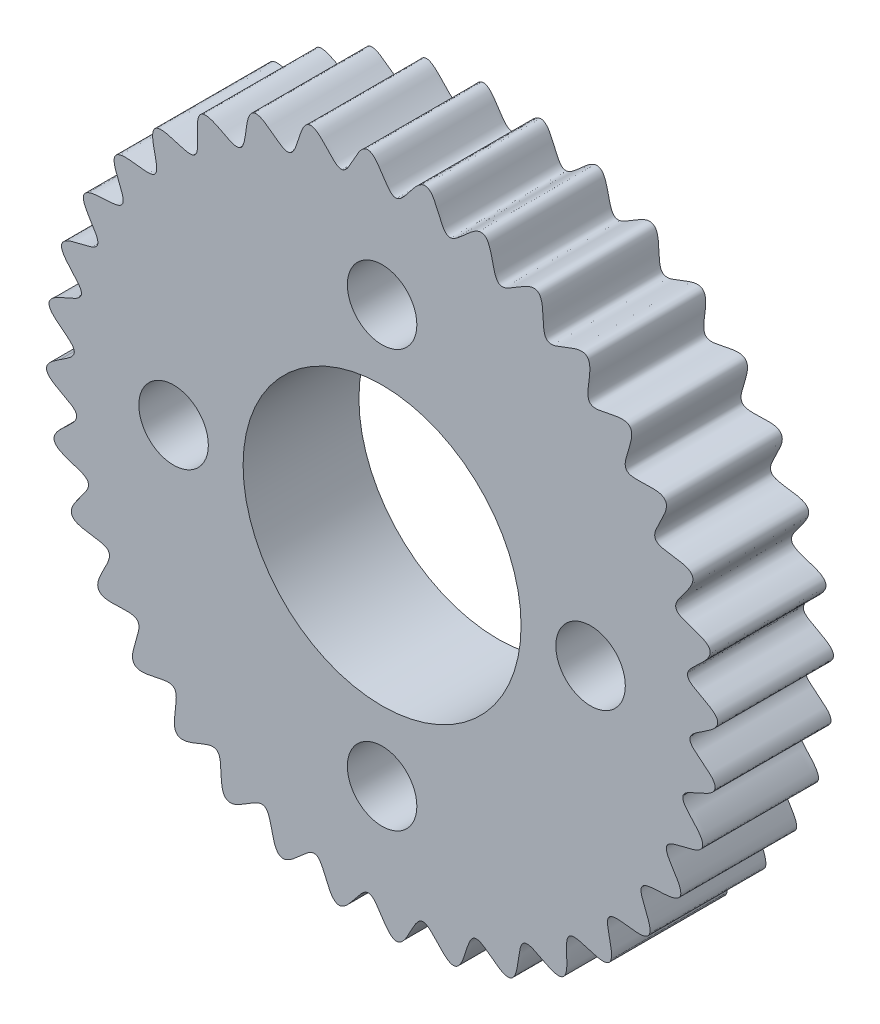
SolidWorks part; units mm, degrees
ref_plane "前视基准面" through (0, 0, 0) normal (0, 0, 1) x (1, 0, 0)
ref_plane "上视基准面" through (0, 0, 0) normal (0, 1, 0) x (1, 0, 0)
ref_plane "右视基准面" through (0, 0, 0) normal (1, 0, 0) x (0, 0, -1)
sketch "草图1" plane through (0, 0, 0) normal (0, 0, 1) x (1, 0, 0)
  circle A0 centre (0, 0) radius 12
  spline S0 degree 4 number of poles 648 (27.5248, -8.9434) -> (-25.354, -8.238) construction
  spline S1 degree 4 number of poles 542 (27.8, 0) -> (-27.8, 0)
  spline S2 degree 4 number of poles 650 (-27.5248, 8.9434) -> (25.354, 8.238) construction
  spline S3 degree 4 number of poles 545 (-27.8, 0) -> (27.8, 0)
extrude "凸台-拉伸1" add sketch "草图1" along normal blind 10
sketch "草图2" plane through (0, 0, 0) normal (0, 0, 1) x (1, 0, 0)
  circle A1 centre (18, 0) radius 3
  circle A2 centre (0, -18) radius 3
  circle A3 centre (-18, 0) radius 3
  circle A4 centre (0, 18) radius 3
  point P12 (0, 0)
  dimension "D1" = 4
extrude "切除-拉伸1" cut sketch "草图2" along normal blind 10
